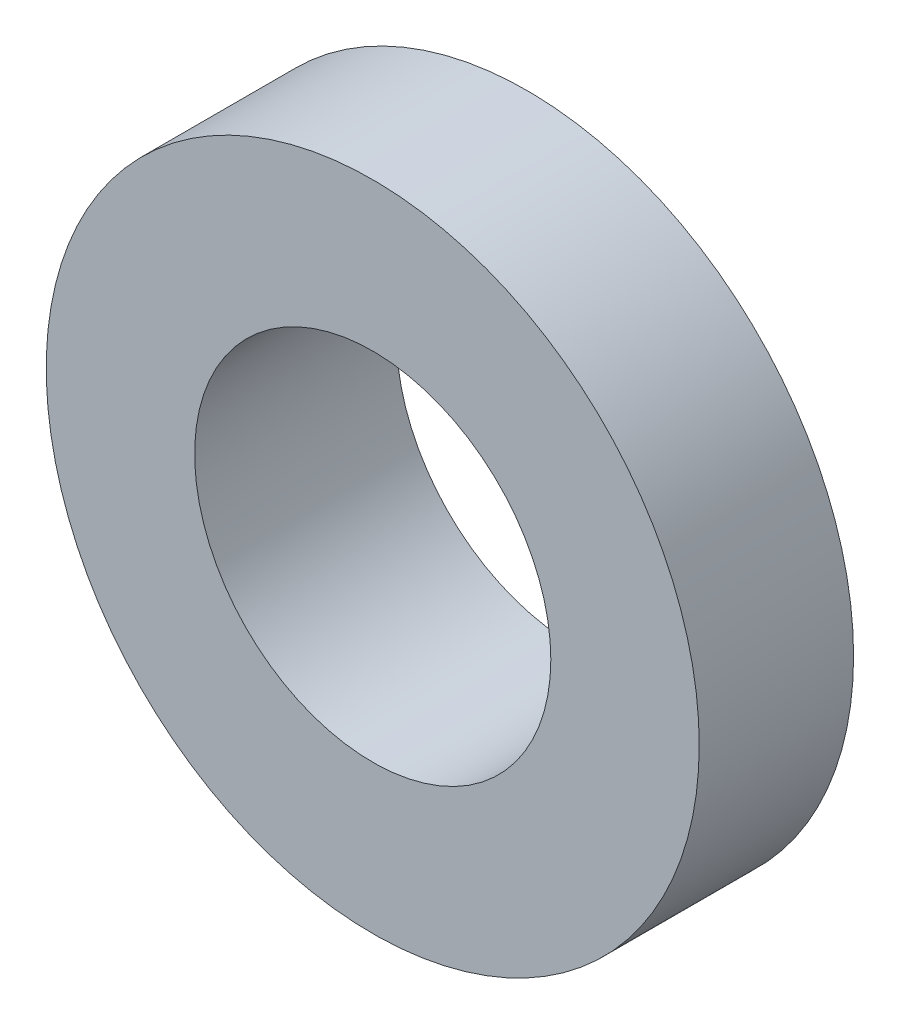
SolidWorks part; units mm, degrees
material "1.3505 (100Cr6) hardened 60 HRC"
ref_plane "Front Plane" through (0, 0, 0) normal (0, 0, 1) x (1, 0, 0)
ref_plane "Top Plane" through (0, 0, 0) normal (0, 1, 0) x (1, 0, 0)
ref_plane "Right Plane" through (0, 0, 0) normal (1, 0, 0) x (0, 0, -1)
sketch "Sketch1" plane through (0, 0, 0) normal (0, 1, 0) x (1, 0, 0)
  line L0 (15, 0) -> (19.5, 0)
  line L1 (19.5, 0) -> (23.5, -4)
  line L2 (23.5, -4) -> (27.5, -4)
  line L3 (27.5, -4) -> (27.5, -17)
  line L4 (27.5, -17) -> (15, -17)
  line L5 (15, -17) -> (15, 0)
  line L6 (0, -150) -> (0, 150) construction
revolve "REV_32006X_Envelope_cone_back_at_z0" add sketch "Sketch1" angle 360 about L6
